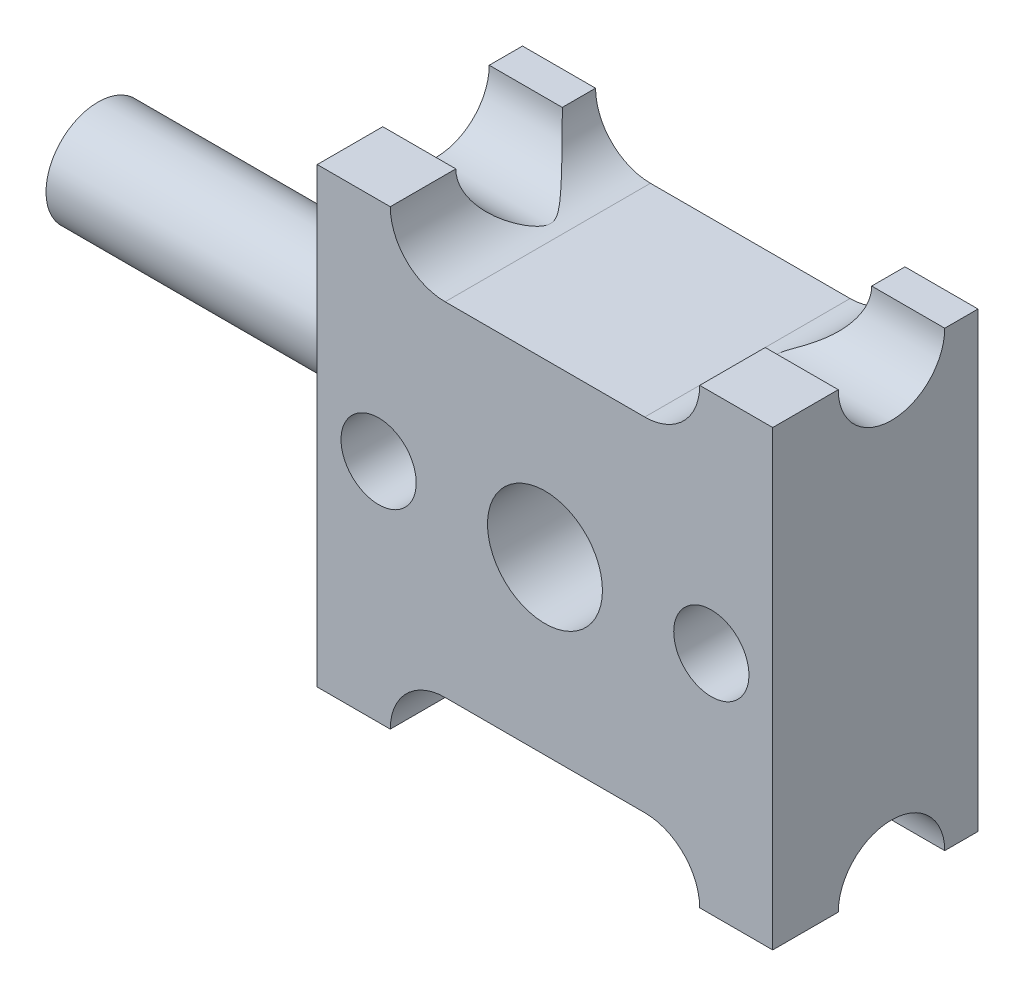
SolidWorks part; units mm, degrees
ref_plane "Front Plane" through (0, 0, 0) normal (0, 0, 1) x (1, 0, 0)
ref_plane "Top Plane" through (0, 0, 0) normal (0, 1, 0) x (1, 0, 0)
ref_plane "Right Plane" through (0, 0, 0) normal (1, 0, 0) x (0, 0, -1)
sketch "Sketch1" plane through (0, 0, 0) normal (0, 0, 1) x (1, 0, 0)
  line L1 (-6.8453, 6.8) -> (6.8453, 6.8)
  line L2 (-6.8453, 6.8) -> (-6.8453, -6.8)
  line L3 (-6.8453, -6.8) -> (6.8453, -6.8)
  line L4 (6.8453, 6.8) -> (6.8453, -6.8)
  line L5 (-6.8453, 6.8) -> (6.8453, -6.8) construction
  line L6 (-6.8453, -6.8) -> (6.8453, 6.8) construction
  point P0 (0, 0)
  dimension "D1" = 13.6906
  dimension "D2" = 13.6
extrude "Boss-Extrude1" add sketch "Sketch1" along normal blind 6.17
sketch "Sketch2" plane through (6.8453, 0, 0) normal (1, 0, 0) x (0, 0, -1)
  line L0 (-6.17, 6.8) -> (0, 6.8) construction
  line L1 (0, -6.8) -> (0, 6.8) construction
  line L2 (-6.17, 0) -> (0, 0) construction
  line L3 (-6.17, -6.8) -> (-6.17, 6.8) construction
  circle A0 centre (-2.6, 6.8) radius 1.6
  circle A1 centre (-2.6, -6.8) radius 1.6
  dimension "D2" = 3.2
  dimension "D1" = 2.6
extrude "Cut-Extrude1" cut sketch "Sketch2" against normal through all
sketch "Sketch3" plane through (0, 0, 6.17) normal (0, 0, 1) x (1, 0, 0)
  line L0 (6.8453, 6.8) -> (-6.8453, 6.8) construction
  line L1 (-3, 6.8) -> (3, 6.8)
  line L2 (-3, 6.8) -> (-3, 5.15)
  line L3 (-3, 5.15) -> (3, 5.15)
  line L4 (3, 6.8) -> (3, 5.15)
  line L5 (0, 5.15) -> (0, 7.1831) construction
  line L6 (-6.8453, 0) -> (0, 5.15) construction
  line L7 (-6.8453, 6.8) -> (-6.8453, -6.8) construction
  line L8 (0, 5.15) -> (6.8453, 0) construction
  line L9 (6.8453, -6.8) -> (6.8453, 6.8) construction
  line L10 (-6.8453, 0) -> (6.8453, 0) construction
  line L11 (0, -5.15) -> (6.8453, 0) construction
  line L12 (-6.8453, 0) -> (0, -5.15) construction
  line L13 (0, -5.15) -> (0, -7.1831) construction
  line L14 (3, -6.8) -> (3, -5.15)
  line L15 (-3, -5.15) -> (3, -5.15)
  line L16 (-3, -6.8) -> (-3, -5.15)
  line L17 (-3, -6.8) -> (3, -6.8)
  line L18 (-4.65, 6.8) -> (4.65, 6.8)
  line L19 (-3, -6.8) -> (3, -6.8)
  arc A0 (3, 5.15) -> (4.65, 6.8) centre (3, 6.8) ccw
  arc A1 (-3, 5.15) -> (-4.65, 6.8) centre (-3, 6.8) cw
  arc A2 (-3, -5.15) -> (-4.65, -6.8) centre (-3, -6.8) ccw
  arc A3 (3, -5.15) -> (4.65, -6.8) centre (3, -6.8) cw
  line M9 (6.8453, 6.8) -> (-6.8453, 6.8)
  line M11 (-6.8453, -6.8) -> (6.8453, -6.8)
  dimension "D2" = 1.65
  dimension "D1" = 1.65
  dimension "D3" = 6
extrude "Cut-Extrude2" cut sketch "Sketch3" against normal through all contours A1 L2 M9 | L4 L2 L3 M9 | L4 A0 M9 | A3 L14 M11 | L16 L14 L15 M11 | L16 A2 M11
sketch "Sketch4" plane through (0, 0, 6.17) normal (0, 0, 1) x (1, 0, 0)
  circle A0 centre (0, 0) radius 1.7272
  dimension "D1" = 3.4544
extrude "Cut-Extrude3" cut sketch "Sketch4" against normal through all
sketch "Sketch5" plane through (-6.8453, 0, 0) normal (-1, 0, 0) x (0, 0, 1)
  line L0 (2.6, 5.2) -> (2.6, -5.2) construction
  circle A0 centre (2.6, 0) radius 1.5621
  arc A2 (1, 6.8) -> (4.2, 6.8) centre (2.6, 6.8) ccw construction
  arc A3 (4.2, -6.8) -> (1, -6.8) centre (2.6, -6.8) ccw construction
  dimension "D1" = 3.1242
extrude "Boss-Extrude2" add sketch "Sketch5" along normal blind 10.16
sketch "Sketch6" plane through (0, 0, 6.17) normal (0, 0, 1) x (1, 0, 0)
  line L0 (0, 5.15) -> (0, -5.15) construction
  line L1 (-3, 5.15) -> (3, 5.15) construction
  line L2 (-3, -5.15) -> (3, -5.15) construction
  circle A0 centre (-5, 0) radius 1.1303
  circle A1 centre (5, 0) radius 1.1303
  dimension "D1" = 2.2606
  dimension "D2" = 10
extrude "Cut-Extrude4" cut sketch "Sketch6" against normal through all
